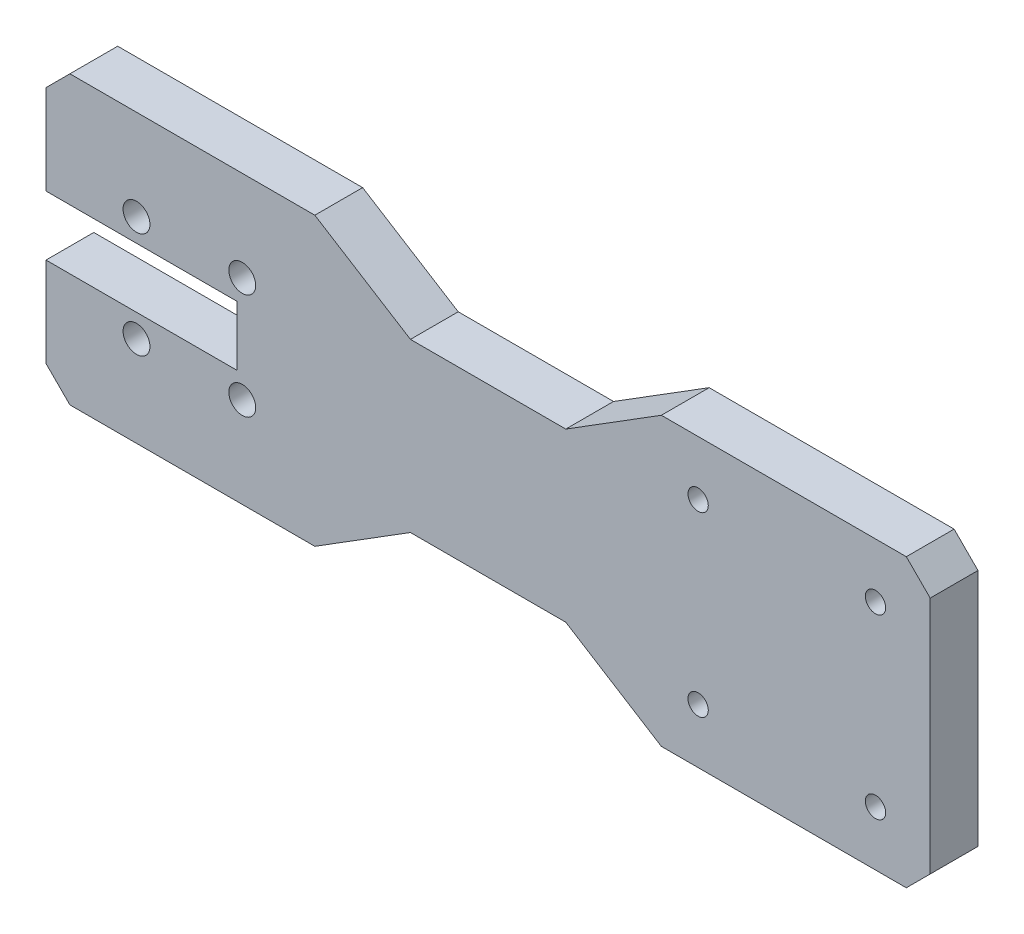
SolidWorks part; units mm, degrees
ref_plane "前视基准面" through (0, 0, 0) normal (0, 0, 1) x (1, 0, 0)
ref_plane "上视基准面" through (0, 0, 0) normal (0, 1, 0) x (1, 0, 0)
ref_plane "右视基准面" through (0, 0, 0) normal (1, 0, 0) x (0, 0, -1)
other "Configuration Table"
sketch "草图1" plane through (0, 0, 0) normal (0, 0, 1) x (1, 0, 0)
  line L0 (-24, -20) -> (-20, -24)
  line L1 (-20, -24) -> (21, -24)
  line L2 (21, -24) -> (37, -14)
  line L3 (37, -14) -> (63, -14)
  line L4 (63, -14) -> (79, -24)
  line L5 (79, -24) -> (120, -24)
  line L6 (120, -24) -> (124, -20)
  line L7 (124, -20) -> (124, 20)
  line L8 (124, 20) -> (120, 24)
  line L9 (120, 24) -> (79, 24)
  line L10 (79, 24) -> (63, 14)
  line L11 (63, 14) -> (37, 14)
  line L12 (37, 14) -> (21, 24)
  line L13 (21, 24) -> (-20, 24)
  line L14 (-20, 24) -> (-24, 20)
  line L15 (-24, 20) -> (-24, 5)
  line L16 (-24, 5) -> (8, 5)
  line L17 (8, 5) -> (8, -5)
  line L18 (8, -5) -> (-24, -5)
  line L19 (-24, -5) -> (-24, -20)
  circle A0 centre (-8.85, -8.85) radius 2.25
  circle A1 centre (-8.85, 8.85) radius 2.25
  circle A2 centre (8.85, -8.85) radius 2.25
  circle A3 centre (8.85, 8.85) radius 2.25
  circle A4 centre (85.155, -14.845) radius 1.7
  circle A5 centre (85.155, 14.845) radius 1.7
  circle A6 centre (114.845, -14.845) radius 1.7
  circle A7 centre (114.845, 14.845) radius 1.7
extrude "板体与通孔" add sketch "草图1" along normal blind 8 from offset 0
